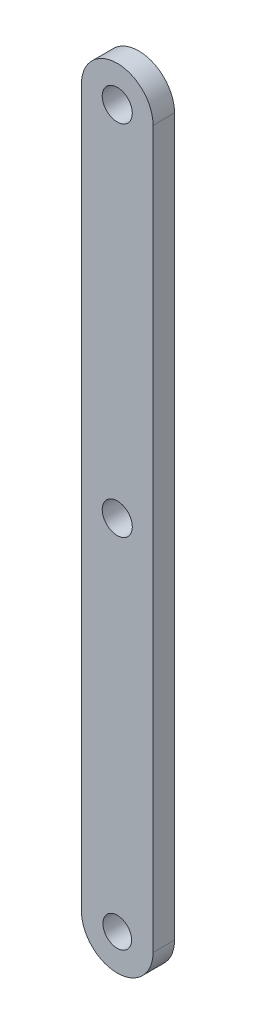
SolidWorks part; units mm, degrees
material "Zoltek Panex 33"
ref_plane "前视基准面" through (0, 0, 0) normal (0, 0, 1) x (1, 0, 0)
ref_plane "上视基准面" through (0, 0, 0) normal (0, 1, 0) x (1, 0, 0)
ref_plane "右视基准面" through (0, 0, 0) normal (1, 0, 0) x (0, 0, -1)
sketch "草图1" plane through (0, 0, 0) normal (0, 0, 1) x (1, 0, 0)
  line L0 (0, 0) -> (0, 50) construction
  line L1 (-2.5, 0) -> (-2.5, 50)
  line L2 (2.5, 0) -> (2.5, 50)
  circle A0 centre (0, 0) radius 1
  arc A2 (-2.5, 0) -> (2.5, 0) centre (0, 0) ccw
  arc A3 (2.5, 50) -> (-2.5, 50) centre (0, 50) ccw
  circle A4 centre (0, 50) radius 1.05
  circle A5 centre (0, 25) radius 1.05
  point P4 (0, 25)
  dimension "D1" = 2
  dimension "D2" = 2.1
  dimension "D3" = 2.5
  dimension "D5" = 2.1
  dimension "D4" = 50
extrude "凸台-拉伸1" add sketch "草图1" along normal blind 1.5
